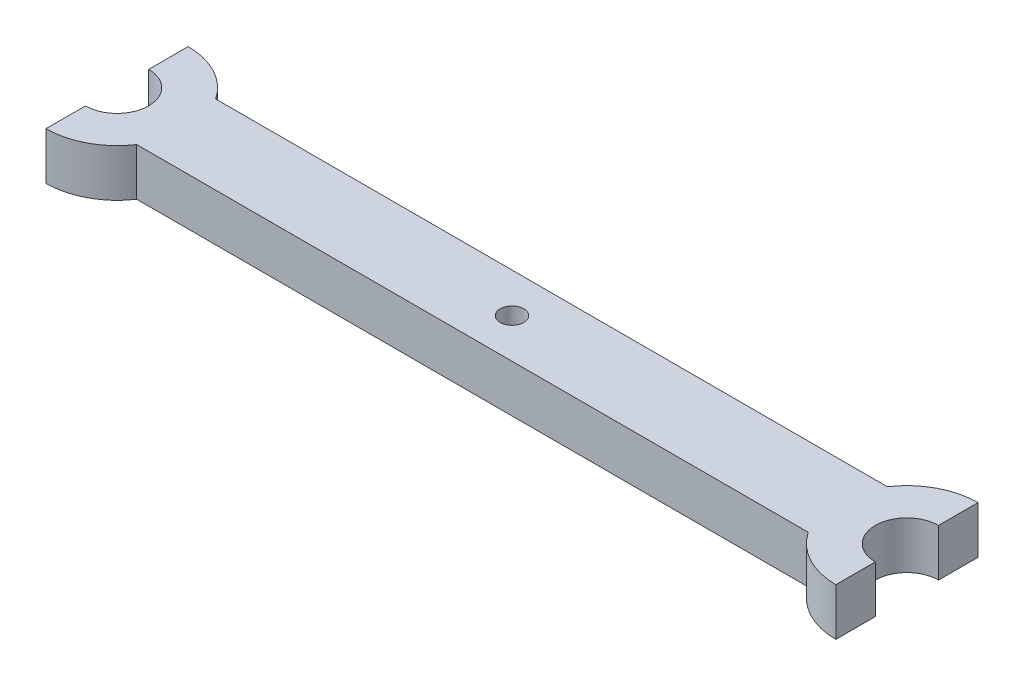
SolidWorks part; units mm, degrees
ref_plane "Front Plane" through (0, 0, 0) normal (0, 0, 1) x (1, 0, 0)
ref_plane "Top Plane" through (0, 0, 0) normal (0, 1, 0) x (1, 0, 0)
ref_plane "Right Plane" through (0, 0, 0) normal (1, 0, 0) x (0, 0, -1)
sketch "Sketch1" plane through (0, 0, 0) normal (0, 1, 0) x (1, 0, 0)
  line L0 (-50, 4) -> (-50, 9)
  line L1 (-50, -4) -> (-50, -9)
  line L2 (-42.5167, -5) -> (42.5167, -5)
  line L3 (-42.5167, 5) -> (42.5167, 5)
  line L4 (50, 4) -> (50, 9)
  line L5 (50, -4) -> (50, -9)
  line L6 (-3.3, 0) -> (3.3, 0) construction
  line L7 (0, -3.3) -> (0, 3.3) construction
  arc A0 (-50, -4) -> (-50, 4) centre (-50, 0) ccw
  arc A1 (-50, 9) -> (-42.5167, 5) centre (-50, 0) cw
  arc A2 (-50, -9) -> (-42.5167, -5) centre (-50, 0) ccw
  arc A3 (50, 4) -> (50, -4) centre (50, 0) ccw
  arc A4 (50, 9) -> (42.5167, 5) centre (50, 0) ccw
  arc A5 (50, -9) -> (42.5167, -5) centre (50, 0) cw
  dimension "D1" = 4
  dimension "D2" = 5
  dimension "D3" = 4
  dimension "D4" = 5
  dimension "D7" = 50
  dimension "D5" = 5
  dimension "D6" = 5
  dimension "D8" = 50
extrude "Boss-Extrude1" add sketch "Sketch1" along normal blind 6
sketch "Sketch2" plane through (0, 6, 0) normal (0, 1, 0) x (1, 0, 0)
  circle A0 centre (0, 0) radius 1.5
  dimension "D1" = 3
extrude "Cut-Extrude1" cut sketch "Sketch2" against normal through all
equation "\"M3_d\"= \"M3_d_laser@troublemaker.Assembly\""
equation "\"housing_t\"= \"housing_t_glob@troublemaker.Assembly\""
equation "\"D1@Boss-Extrude1\"=\"housing_t\""
equation "\"D1@Sketch2\"=\"M3_d\""
